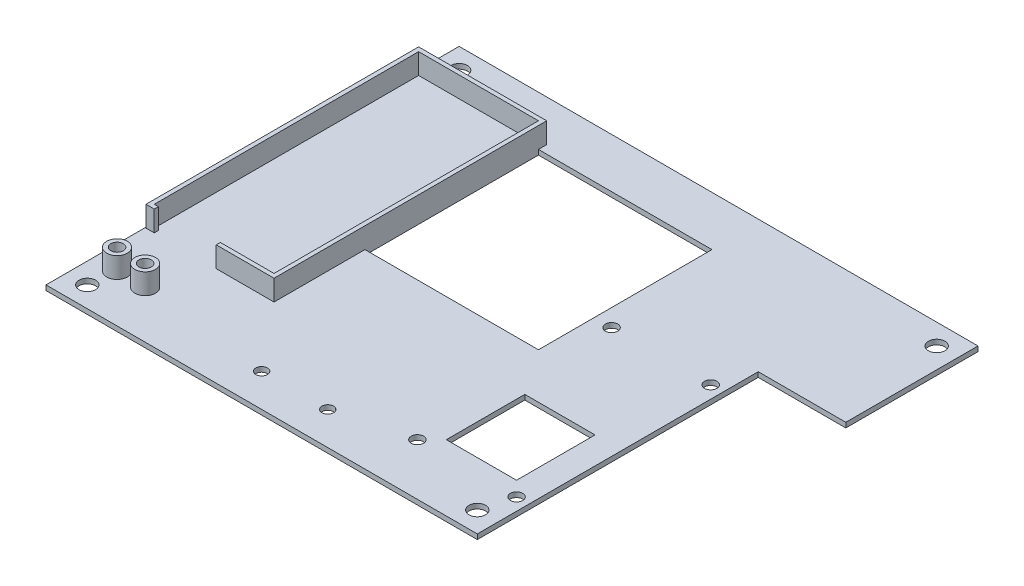
SolidWorks part; units mm, degrees
ref_plane "前视基准面" through (0, 0, 0) normal (0, 0, 1) x (1, 0, 0)
ref_plane "上视基准面" through (0, 0, 0) normal (0, 1, 0) x (1, 0, 0)
ref_plane "右视基准面" through (0, 0, 0) normal (1, 0, 0) x (0, 0, -1)
sketch "草图1" plane through (0, 0, 0) normal (0, 1, 0) x (1, 0, 0)
  line L0 (104.4, 68) -> (125.6, 68)
  line L1 (0, 0) -> (104.4, 0)
  line L2 (0, 0) -> (0, 100)
  line L3 (0, 100) -> (125.6, 100)
  line L4 (104.4, 0) -> (104.4, 68)
  line L5 (125.6, 68) -> (125.6, 100)
  line L6 (0, 50) -> (149.2706, 50) construction
  line L7 (62.8, 100) -> (62.8, 77.5333) construction
  line L8 (52.2, 0) -> (52.2, 110.7171) construction
  line L9 (31.2, 46) -> (73.2, 46)
  line L10 (73.2, 46) -> (73.2, 88)
  line L11 (73.2, 88) -> (31.2, 88)
  line L12 (31.2, 46) -> (31.2, 88)
  line L13 (89.4, 62.3887) -> (89.4, 10) construction
  line L14 (89.4, 10) -> (104.4, 10) construction
  line L15 (101.4, 12.5) -> (101.4, 59.5) construction
  line L16 (80.9, 16) -> (97.9, 16)
  line L17 (97.9, 16) -> (97.9, 35)
  line L18 (97.9, 35) -> (80.9, 35)
  line L19 (80.9, 16) -> (80.9, 35)
  line L20 (40.2713, 8) -> (62.8, 8) construction
  circle A0 centre (5, 5) radius 2
  circle A1 centre (5, 95) radius 2
  circle A2 centre (120.6, 95) radius 2
  circle A3 centre (99.4, 5) radius 2
  circle A4 centre (101.4, 12.5) radius 1.5
  circle A5 centre (77.4, 12.5) radius 1.5
  circle A6 centre (101.4, 59.5) radius 1.5
  circle A7 centre (77.4, 59.5) radius 1.5
  circle A8 centre (60.2, 8) radius 1.4
  circle A9 centre (44.2, 8) radius 1.4
  point P26 (52.2, 46)
  point P27 (52.2, 88)
  point P43 (89.4, 16)
  point P44 (89.4, 35)
  point P50 (60.2, 5.0004)
  dimension "D5" = 4
  dimension "D6" = 5
  dimension "D11" = 3
  dimension "D12" = 3
  dimension "D13" = 24
  dimension "D14" = 47
  dimension "D15" = 2.5
  dimension "D21" = 2.8
  dimension "D22" = 16
  dimension "D1" = 104.4
  dimension "D2" = 100
  dimension "D3" = 125.6
  dimension "D4" = 68
  dimension "D7" = 5
  dimension "D8" = 42
  dimension "D9" = 42
  dimension "D10" = 88
  dimension "D16" = 17
  dimension "D17" = 19
  dimension "D18" = 6
  dimension "D19" = 15
  dimension "D20" = 10
  dimension "D23" = 8
extrude "凸台-拉伸1" add sketch "草图1" along normal blind 1.2
sketch "草图2" plane through (0, 1.2, 0) normal (0, 1, 0) x (1, 0, 0)
  line L0 (1.2, 89) -> (1.2, 25)
  line L1 (0.2, 90) -> (31.2, 90)
  line L2 (0.2, 90) -> (0.2, 24)
  line L3 (0.2, 24) -> (31.2, 24)
  line L4 (31.2, 90) -> (31.2, 24)
  line L5 (1.2, 25) -> (30.2, 25)
  line L6 (30.2, 89) -> (30.2, 25)
  line L7 (1.2, 89) -> (30.2, 89)
  line L8 (125.6, 100) -> (0, 100) construction
  line L9 (31.2, 88) -> (31.2, 46) construction
  line L10 (0, 11.5) -> (33.2423, 11.5) construction
  line L11 (0, 100) -> (0, 0) construction
  circle A0 centre (5.7, 11.5) radius 1.5
  circle A1 centre (12.5, 11.5) radius 1.5
  circle A2 centre (12.5, 11.5) radius 2.5
  circle A3 centre (5.7, 11.5) radius 2.5
  dimension "D5" = 3
  dimension "D6" = 3
  dimension "D7" = 6.8
  dimension "D9" = 13.5
  dimension "D2" = 29
  dimension "D3" = 64
  dimension "D4" = 10
  dimension "D8" = 4.5
  dimension "D1" = 1
  dimension "D10" = 1
extrude "凸台-拉伸2" add sketch "草图2" along normal blind 5
sketch "草图3" plane through (0, 6.2, 0) normal (0, 1, 0) x (1, 0, 0)
  line L0 (0.2, 24) -> (31.2, 24) construction
  line L1 (2.2, 27) -> (17.2, 27)
  line L2 (2.2, 27) -> (2.2, 24)
  line L3 (2.2, 24) -> (17.2, 24)
  line L4 (17.2, 27) -> (17.2, 24)
  line L5 (1.2, 89) -> (1.2, 25) construction
  dimension "D1" = 15
  dimension "D2" = 1
extrude "切除-拉伸1" cut sketch "草图3" against normal blind 5
